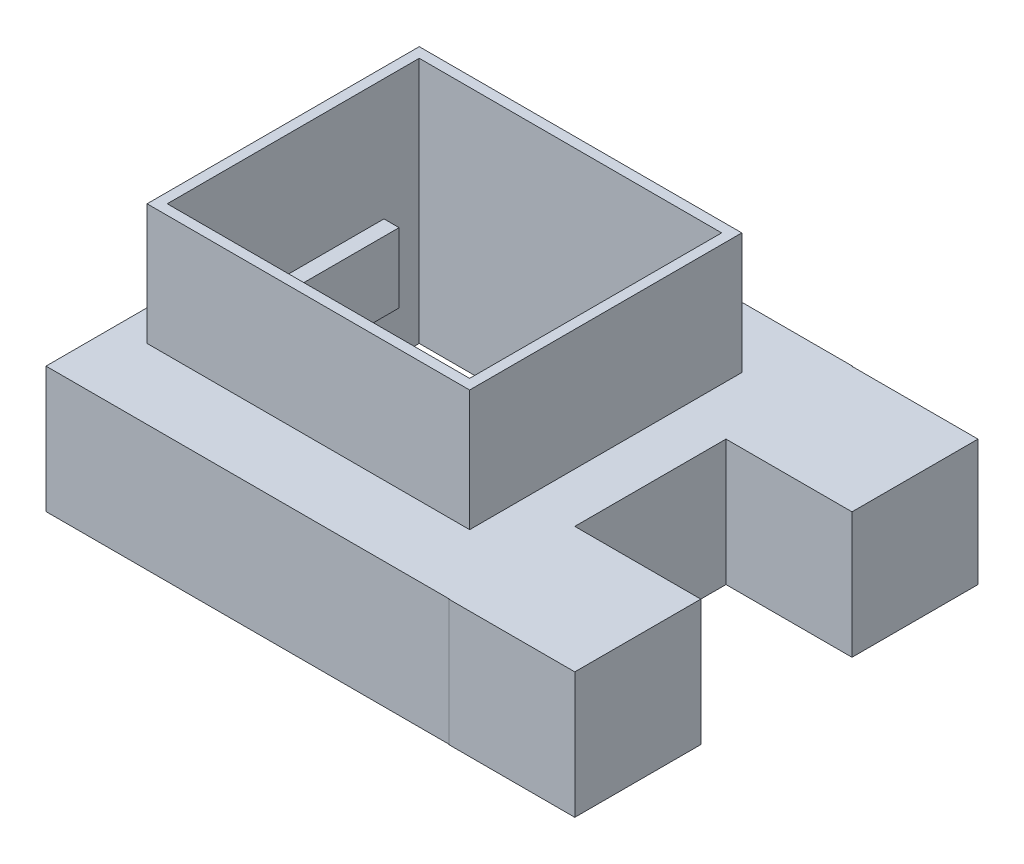
SolidWorks part; units mm, degrees
ref_plane "Front Plane" through (0, 0, 0) normal (0, 0, 1) x (1, 0, 0)
ref_plane "Top Plane" through (0, 0, 0) normal (0, 1, 0) x (1, 0, 0)
ref_plane "Right Plane" through (0, 0, 0) normal (1, 0, 0) x (0, 0, -1)
sketch "Sketch3" plane through (0, 0, 0) normal (0, 1, 0) x (1, 0, 0)
  line L13 (193.1865, -45.9227) -> (-166.5798, 39.5979) construction
  line L14 (193.1865, 3954.0773) -> (175.1011, 3583.9103) construction
  line L15 (-3806.8135, 3954.0773) -> (193.1865, 3954.0773)
  line L16 (-3806.8135, 3954.0773) -> (-3806.8135, -45.9227)
  line L17 (-3806.8135, -45.9227) -> (193.1865, -45.9227)
  line L18 (193.1865, 3954.0773) -> (193.1865, -45.9227)
  point P0 (0, 0)
  point P1 (0, 0)
extrude "Boss-Extrude1" add sketch "Sketch3" along normal blind 1250
sketch "Sketch4" plane through (0, 1250, 0) normal (0, 1, 0) x (1, 0, 0)
  line L7 (-300, 650) -> (-3500, 650)
  line L8 (-300, 650) -> (-300, 3350)
  line L9 (-300, 3350) -> (-3500, 3350)
  line L10 (-3500, 650) -> (-3500, 3350)
  line L11 (-300, 650) -> (-3500, 3350) construction
  line L12 (-300, 3350) -> (-3500, 650) construction
  point P0 (0, 0)
  point P1 (0, 0)
  point P2 (-1738.1201, 2035.0374)
  point P3 (-1846.0668, 1985.9707)
  point P6 (-1900, 2000)
extrude "Boss-Extrude2" add sketch "Sketch4" along normal blind 1200
sketch "Sketch6" plane through (0, 2450, 0) normal (0, 1, 0) x (1, 0, 0)
  line L1 (-400, 750) -> (-3400, 750)
  line L2 (-400, 750) -> (-400, 3250)
  line L3 (-400, 3250) -> (-3400, 3250)
  line L4 (-3400, 750) -> (-3400, 3250)
  line L5 (-400, 750) -> (-3400, 3250) construction
  line L6 (-400, 3250) -> (-3400, 750) construction
  point P0 (-1900, 2000)
  point P5 (0, 0)
  point P6 (0, 0)
  point P7 (-1811.7202, 2005.5974)
  point P8 (0, 0)
extrude "Cut-Extrude1" cut sketch "Sketch6" against normal through all
sketch "Sketch8" plane through (-3400, 0, 0) normal (1, 0, 0) x (0, 0, -1)
  line L1 (2900, 555) -> (900, 555)
  line L2 (2900, 555) -> (2900, 1245)
  line L3 (2900, 1245) -> (900, 1245)
  line L4 (900, 555) -> (900, 1245)
  line L5 (2900, 555) -> (900, 1245) construction
  line L6 (2900, 1245) -> (900, 555) construction
  point P0 (1900, 900)
  point P5 (1904.09, 899.9764)
  point P6 (1889.6215, 340.2356)
sketch "Sketch9" plane through (-400, 0, 0) normal (-1, 0, 0) x (0, 0, 1)
  line L1 (-900, 555) -> (-2900, 555)
  line L2 (-900, 555) -> (-900, 1245)
  line L3 (-900, 1245) -> (-2900, 1245)
  line L4 (-2900, 555) -> (-2900, 1245)
  line L5 (-900, 555) -> (-2900, 1245) construction
  line L6 (-900, 1245) -> (-2900, 555) construction
  point P0 (-1900, 900)
extrude "Boss-Extrude8" add sketch "Sketch9" along normal blind 150
extrude "Boss-Extrude9" add sketch "Sketch8" along normal blind 150
sketch "Sketch13" plane through (193.1865, 0, 0) normal (1, 0, 0) x (0, 0, -1)
  line L1 (-50, 1250) -> (1200, 1250)
  line L2 (-50, 1250) -> (-50, 0)
  line L3 (-50, 0) -> (1200, 0)
  line L4 (1200, 1250) -> (1200, 0)
  line L5 (-50, 1250) -> (1200, 0) construction
  line L6 (-50, 0) -> (1200, 1250) construction
  point P0 (575, 625)
  point P5 (0, 0)
extrude "Boss-Extrude5" add sketch "Sketch13" along normal blind 1250
sketch "Sketch14" plane through (193.1865, 0, 0) normal (1, 0, 0) x (0, 0, -1)
  line L1 (2700, 1250) -> (3950, 1250)
  line L2 (2700, 1250) -> (2700, 0)
  line L3 (2700, 0) -> (3950, 0)
  line L4 (3950, 1250) -> (3950, 0)
  line L5 (2700, 1250) -> (3950, 0) construction
  line L6 (2700, 0) -> (3950, 1250) construction
  point P0 (3325, 625)
  point P5 (0, 0)
  point P6 (0, 0)
extrude "Boss-Extrude6" add sketch "Sketch14" along normal blind 1250
scale "Scale1" scale about centroid uniform scaling yes scale factor 0.01
